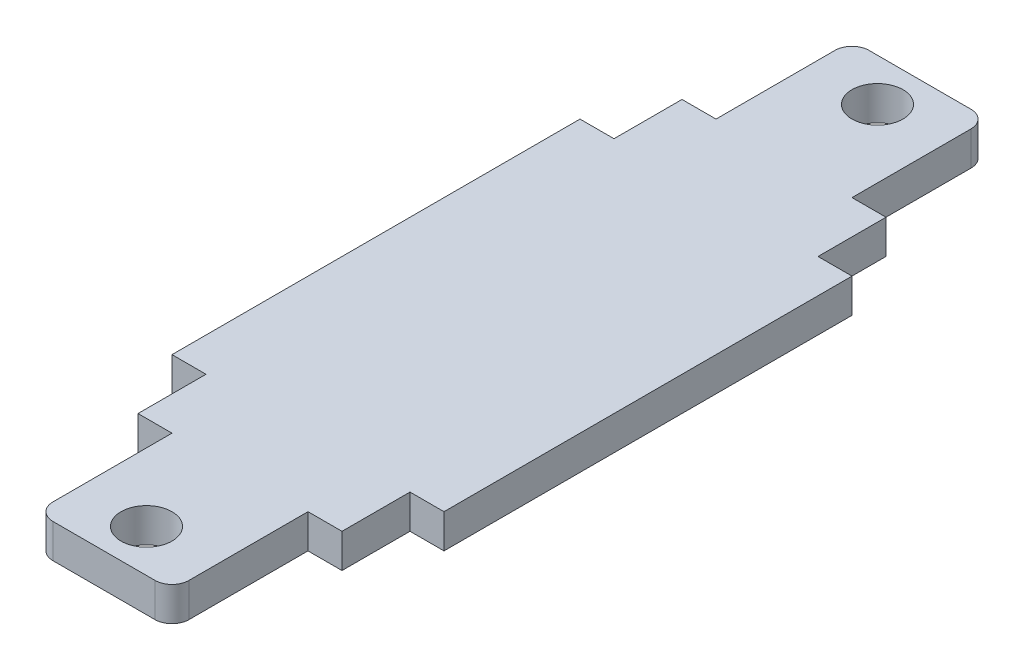
SolidWorks part; units mm, degrees
ref_plane "Front Plane" through (0, 0, 0) normal (0, 0, 1) x (1, 0, 0)
ref_plane "Top Plane" through (0, 0, 0) normal (0, 1, 0) x (1, 0, 0)
ref_plane "Right Plane" through (0, 0, 0) normal (1, 0, 0) x (0, 0, -1)
sketch "Sketch1" plane through (0, 0, 0) normal (0, 0, 1) x (1, 0, 0)
  line L0 (191.9163, 258.3186) -> (191.9163, 313.8768) construction
  line L1 (191.9163, 371.0268) -> (166.5163, 371.0268)
  line L2 (191.9163, 371.0268) -> (191.9163, 374.2018)
  line L3 (191.9163, 374.2018) -> (166.5163, 374.2018)
  line L4 (166.5163, 371.0268) -> (166.5163, 374.2018)
  dimension "D1" = 3.175
  dimension "D2" = 25.4
extrude "Boss-Extrude1" add sketch "Sketch1" against normal blind 66.675 and the other way blind 9.525 contours L3 L4 L1 L2
sketch "Sketch2" plane through (0, 374.2018, 0) normal (0, 1, 0) x (1, 0, 0)
  line L0 (166.5163, 28.575) -> (191.9163, 28.575)
  line L1 (191.9163, 66.675) -> (166.5163, 66.675) construction
  line L2 (166.5163, 66.675) -> (166.5163, 57.15)
  line L3 (169.6913, 53.975) -> (172.8663, 53.975)
  line L4 (172.8663, 65.0875) -> (172.8663, 53.975)
  line L5 (166.5163, 57.15) -> (166.5163, 47.625)
  line L6 (191.9163, 66.675) -> (191.9163, 53.975)
  line L7 (188.7413, 53.975) -> (185.5663, 53.975)
  line L8 (185.5663, 65.0875) -> (185.5663, 53.975)
  line L9 (174.4538, 66.675) -> (183.9788, 66.675)
  line L10 (166.5163, 66.675) -> (166.5163, 72.354)
  line L11 (166.5163, 72.354) -> (191.9163, 72.354)
  line L12 (191.9163, 66.675) -> (191.9163, 72.354)
  line L13 (166.5163, 47.625) -> (169.6913, 47.625)
  line L14 (169.6913, 53.975) -> (169.6913, 47.625)
  line L16 (191.9163, 53.975) -> (191.9163, 47.625)
  line L17 (191.9163, 47.625) -> (188.7413, 47.625)
  line L18 (188.7413, 53.975) -> (188.7413, 47.625)
  line L19 (166.5163, -9.525) -> (166.5163, 66.675) construction
  line L20 (191.9163, -9.525) -> (191.9163, 66.675) construction
  line L21 (188.7413, 3.175) -> (188.7413, 9.525)
  line L22 (191.9163, 9.525) -> (188.7413, 9.525)
  line L23 (191.9163, 3.175) -> (191.9163, 9.525)
  line L25 (169.6913, 3.175) -> (169.6913, 9.525)
  line L26 (166.5163, 9.525) -> (169.6913, 9.525)
  line L27 (191.9163, -9.525) -> (191.9163, -15.204)
  line L28 (166.5163, -15.204) -> (191.9163, -15.204)
  line L29 (166.5163, -9.525) -> (166.5163, -15.204)
  line L30 (174.4538, -9.525) -> (183.9788, -9.525)
  line L31 (185.5663, -7.9375) -> (185.5663, 3.175)
  line L32 (188.7413, 3.175) -> (185.5663, 3.175)
  line L33 (191.9163, -9.525) -> (191.9163, 3.175)
  line L34 (166.5163, 0) -> (166.5163, 9.525)
  line L35 (172.8663, -7.9375) -> (172.8663, 3.175)
  line L36 (169.6913, 3.175) -> (172.8663, 3.175)
  line L37 (166.5163, -9.525) -> (166.5163, 0)
  arc A0 (183.9788, 66.675) -> (185.5663, 65.0875) centre (183.9788, 65.0875) cw
  arc A1 (174.4538, 66.675) -> (172.8663, 65.0875) centre (174.4538, 65.0875) ccw
  circle A2 centre (179.2163, 62.7062) radius 2.3813
  circle A3 centre (179.2163, -5.5562) radius 2.3813
  arc A4 (174.4538, -9.525) -> (172.8663, -7.9375) centre (174.4538, -7.9375) cw
  arc A5 (183.9788, -9.525) -> (185.5663, -7.9375) centre (183.9788, -7.9375) ccw
  point P14 (185.5663, 66.675)
  point P17 (172.8663, 66.675)
  point P54 (172.8663, -9.525)
  point P55 (185.5663, -9.525)
  line M12 (191.9163, -9.525) -> (191.9163, 66.675)
  line M13 (191.9163, 66.675) -> (166.5163, 66.675)
  line M14 (166.5163, 66.675) -> (166.5163, -9.525)
  line M15 (166.5163, -9.525) -> (191.9163, -9.525)
  dimension "D5" = 1.5875
  dimension "D6" = 4.7625
  dimension "D7" = 3.9688
  dimension "D1" = 6.35
  dimension "D2" = 6.35
  dimension "D3" = 12.7
  dimension "D4" = 12.7
  dimension "D8" = 6.35
  dimension "D9" = 3.175
  dimension "D10" = 3.175
  dimension "D11" = 6.35
  dimension "D12" = 6.35
extrude "Cut-Extrude1" cut sketch "Sketch2" against normal through all contours A1 L13 L14 L3 L4 M13 M14 | L12 L11 L10 M13 | A0 L8 L7 L18 L17 M13 M12 | A2 | A4 L35 L36 L25 L26 M15 M14 | L29 L28 L27 M15 | A5 L22 L21 L32 L31 M15 M12 | A3
